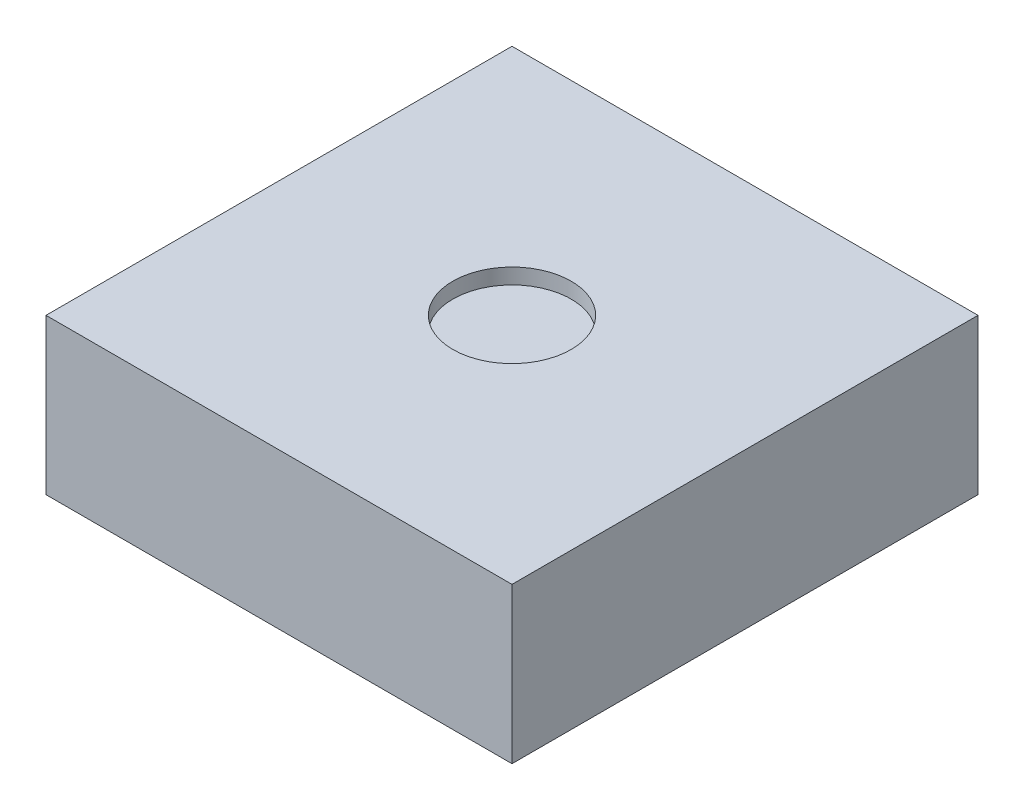
SolidWorks part; units mm, degrees
ref_plane "Front Plane" through (0, 0, 0) normal (0, 0, 1) x (1, 0, 0)
ref_plane "Top Plane" through (0, 0, 0) normal (0, 1, 0) x (1, 0, 0)
ref_plane "Right Plane" through (0, 0, 0) normal (1, 0, 0) x (0, 0, -1)
sketch "Sketch1" plane through (0, 0, 0) normal (0, 1, 0) x (1, 0, 0)
  line L1 (0, 15) -> (0, -15) construction
  line L2 (-15, 0) -> (15, 0) construction
  line L3 (-15, 15) -> (15, 15)
  line L4 (-15, 15) -> (-15, -15)
  line L5 (-15, -15) -> (15, -15)
  line L6 (15, 15) -> (15, -15)
  circle A0 centre (0, 0) radius 15
  point P3 (0, 0)
  dimension "D1" = 30
extrude "Boss-Extrude1" add sketch "Sketch1" along normal blind 10
sketch "Sketch2" plane through (0, 10, 0) normal (0, 1, 0) x (1, 0, 0)
  circle A0 centre (0, 0) radius 3.81
  point P8 (0, 0)
  dimension "D1" = 7.62
extrude "bore" cut sketch "Sketch2" against normal blind 1
equation "\"draft angle\"= 65deg"
equation "\"D3\"= \"draft angle\""
equation "\"altitude\"= cotan ( \"draft angle\" ) * 3 / 2 * .25in"
equation "\"D1\"= 15"
equation "\"D1@Sketch1\"=\"foot diam@table assembly.Assembly\""
equation "\"D1@Sketch2\"=\"bore diam@table assembly.Assembly\""
equation "\"D1@Boss-Extrude1\"=\"foot height@table assembly.Assembly\""
